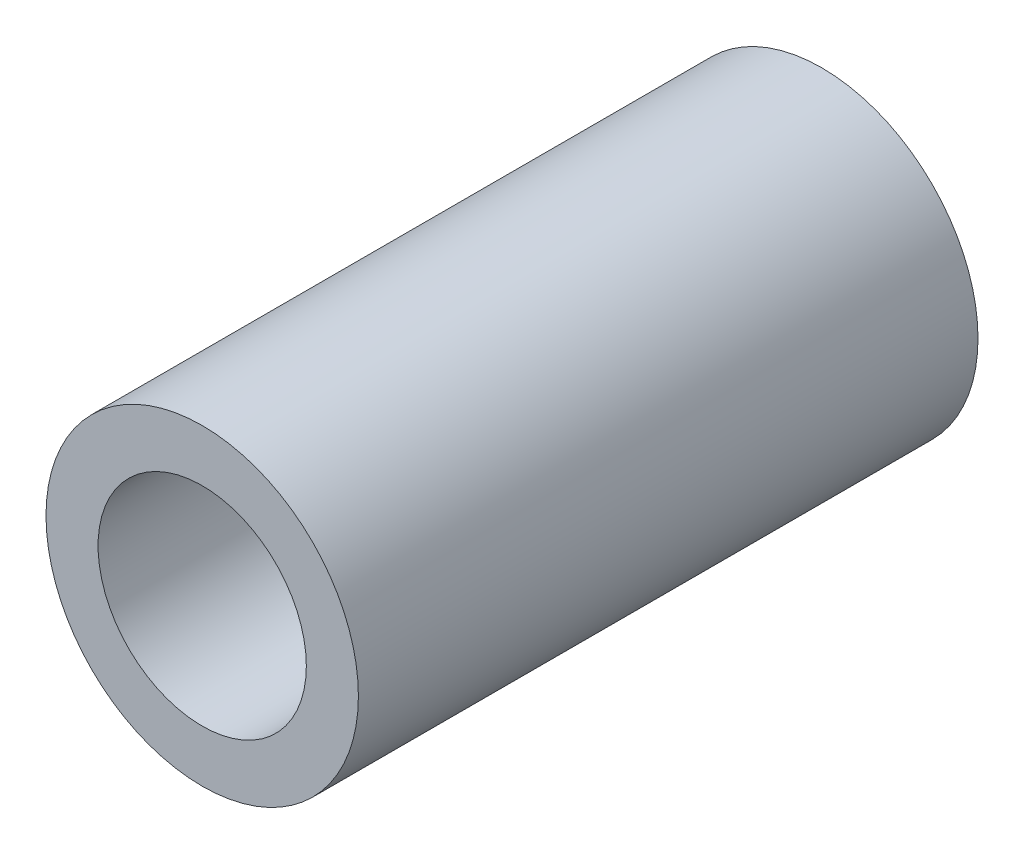
SolidWorks part; units mm, degrees
material "炭素鋼(普通)"
ref_plane "正面" through (0, 0, 0) normal (0, 0, 1) x (1, 0, 0)
ref_plane "平面" through (0, 0, 0) normal (0, 1, 0) x (1, 0, 0)
ref_plane "右側面" through (0, 0, 0) normal (1, 0, 0) x (0, 0, -1)
sketch "ｽｹｯﾁ1" plane through (0, 0, 0) normal (0, 0, 1) x (1, 0, 0)
  circle A0 centre (0, 0) radius 3
  circle A1 centre (0, 0) radius 2
  dimension "D1" = 6
  dimension "D2" = 4
extrude "ﾎﾞｽ - 押し出し1" add sketch "ｽｹｯﾁ1" along normal blind 11.9
